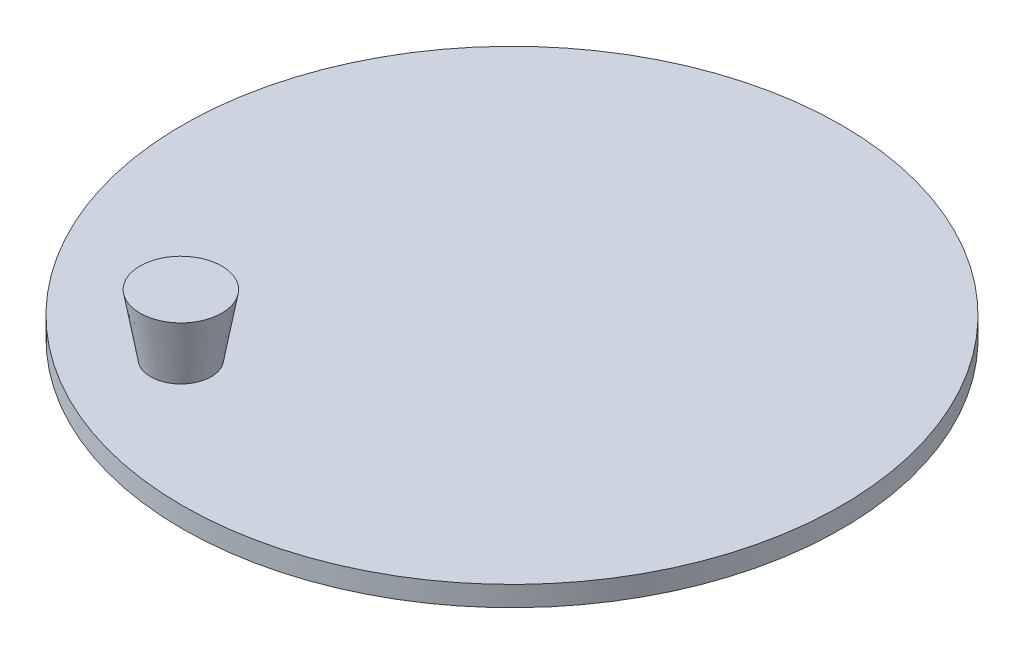
SolidWorks part; units mm, degrees
ref_plane "Front Plane" through (0, 0, 0) normal (0, 0, 1) x (1, 0, 0)
ref_plane "Top Plane" through (0, 0, 0) normal (0, 1, 0) x (1, 0, 0)
ref_plane "Right Plane" through (0, 0, 0) normal (1, 0, 0) x (0, 0, -1)
sketch "Sketch1" plane through (0, 0, 0) normal (0, 1, 0) x (1, 0, 0)
  circle A0 centre (0, 0) radius 16.35
  dimension "D1" = 32.7
extrude "Boss-Extrude1" add sketch "Sketch1" along normal blind 1
sketch "Sketch2" plane through (0, 1, 0) normal (0, 1, 0) x (1, 0, 0)
  circle A0 centre (-6.3217, -10.1055) radius 1.4984
extrude "Boss-Extrude2" add sketch "Sketch2" along normal blind 3 draft 10 draft outward yes
